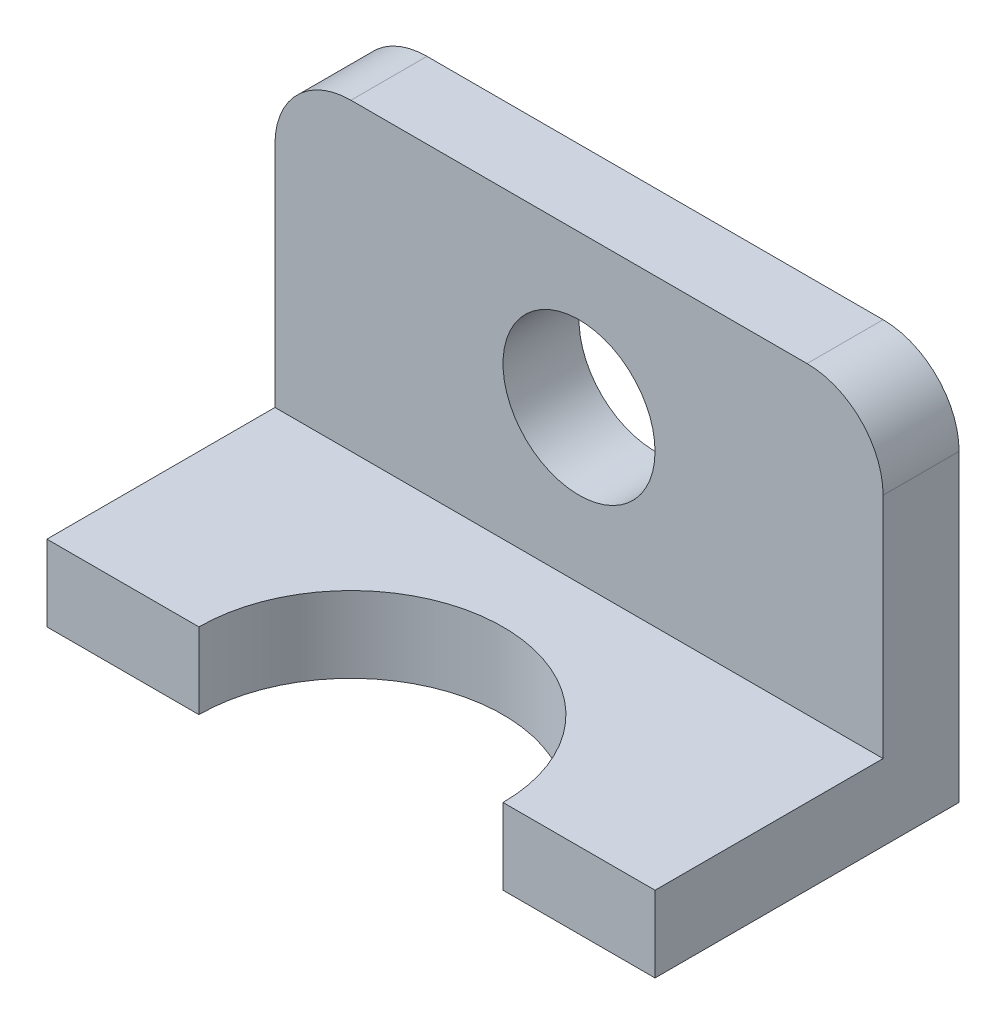
SolidWorks part; units mm, degrees
material "6061 Alloy"
ref_plane "Front Plane" through (0, 0, 0) normal (0, 0, 1) x (1, 0, 0)
ref_plane "Top Plane" through (0, 0, 0) normal (0, 1, 0) x (1, 0, 0)
ref_plane "Right Plane" through (0, 0, 0) normal (1, 0, 0) x (0, 0, -1)
sketch "Croquis1" plane through (0, 0, 0) normal (1, 0, 0) x (0, 0, -1)
  line L0 (0, 0) -> (-50.8, 0)
  line L1 (-50.8, 0) -> (-50.8, 12.7)
  line L2 (-50.8, 12.7) -> (-12.7, 12.7)
  line L3 (-12.7, 12.7) -> (-12.7, 63.5)
  line L4 (-12.7, 63.5) -> (0, 63.5)
  line L5 (0, 63.5) -> (0, 0)
  point P3 (-5.9407, 12.7)
  dimension "D1" = 63.5
  dimension "D2" = 50.8
  dimension "D3" = 12.7
  dimension "D4" = 12.7
extrude "Saliente-Extruir1" add sketch "Croquis1" along normal blind 101.6
sketch "Croquis2" plane through (0, 0, 12.7) normal (0, 0, 1) x (1, 0, 0)
  line L0 (50.8, 63.5) -> (50.8, 12.7) construction
  line L1 (101.6, 63.5) -> (0, 63.5) construction
  line L2 (101.6, 12.7) -> (0, 12.7) construction
  circle A0 centre (50.8, 38.1) radius 12.7
  dimension "D1" = 25.4
extrude "Cortar-Extruir1" cut sketch "Croquis2" against normal blind 101.6 contours A0
sketch "Croquis3" plane through (0, 12.7, 0) normal (0, 1, 0) x (1, 0, 0)
  line L0 (101.6, -50.8) -> (0, -50.8) construction
  circle A0 centre (50.8, -50.8) radius 25.4
  dimension "D1" = 50.8
extrude "Cortar-Extruir2" cut sketch "Croquis3" against normal blind 101.6
fillet "Redondeo2" radius 12.7 2 edges at (101.6, 63.5, 6.35) (0, 63.5, 6.35)
